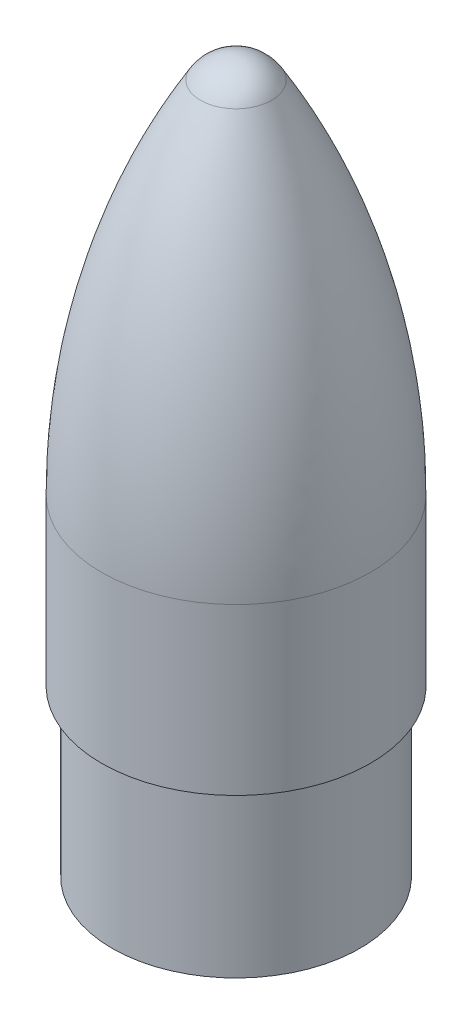
SolidWorks part; units mm, degrees
ref_plane "Front Plane" through (0, 0, 0) normal (0, 0, 1) x (1, 0, 0)
ref_plane "Top Plane" through (0, 0, 0) normal (0, 1, 0) x (1, 0, 0)
ref_plane "Right Plane" through (0, 0, 0) normal (1, 0, 0) x (0, 0, -1)
sketch "Sketch1" plane through (0, 0, 0) normal (0, 1, 0) x (1, 0, 0)
  circle A0 centre (0, 0) radius 38.1
  dimension "D1" = 76.2
extrude "Boss-Extrude1" add sketch "Sketch1" along normal blind 50.8
sketch "Sketch2" plane through (0, 50.8, 0) normal (0, 1, 0) x (1, 0, 0)
  circle A0 centre (0, 0) radius 41.275
  dimension "D1" = 82.55
extrude "Boss-Extrude2" add sketch "Sketch2" along normal blind 50.8 contours A0
sketch "Sketch3" plane through (0, 0, 0) normal (0, 0, 1) x (1, 0, 0)
  line L0 (-41.275, 101.6) -> (-41.275, 203.5852) construction
  line L1 (0, 0) -> (0, 267.966) construction
  line L2 (41.275, 101.6) -> (-41.275, 101.6) construction
  line L3 (0, 214.4291) -> (0, 218.2391)
  line L4 (-41.275, 101.6) -> (-37.465, 101.6)
  line L6 (-37.465, 101.6) -> (-37.465, 203.5852) construction
  arc A2 (-8.1383, 210.2757) -> (0, 214.4291) centre (0, 204.3791) cw
  arc A3 (-10.9151, 212.0314) -> (0, 218.2391) centre (0, 205.539) cw
  spline S0 degree 4 poles (-40.9693, 90.1105) (-40.9822, 90.3534) (-41.0072, 90.8387) (-41.0544, 91.8015) (-41.1162, 93.2573) (-41.1671, 94.6789) (-41.2072, 96.1406) (-41.2386, 97.5282) (-41.2579, 98.8003) (-41.2701, 99.8349) (-41.276, 101.4722) (-41.275, 102.0721) (-41.2687, 103.5121) (-41.2579, 104.3192) (-41.2464, 105.1639) (-41.2283, 106.1358) (-41.2007, 107.3342) (-41.1598, 108.7297) (-41.1008, 110.3354) (-41.0296, 111.9467) (-40.9463, 113.5588) (-40.8509, 115.1695) (-40.7435, 116.7799) (-40.6241, 118.3892) (-40.4598, 120.3997) (-40.2386, 122.8103) (-39.9456, 125.6193) (-39.5628, 128.8241) (-38.8092, 134.4221) (-36.9677, 145.5703) (-33.4913, 160.5237) (-28.3081, 176.2638) (-22.4871, 190.021) (-18.4288, 198.3676) (-16.1932, 202.6623) (-14.6574, 205.4912) (-13.7817, 207.0667) (-13.1957, 208.106) (-12.7072, 208.9626) (-12.3111, 209.651) (-11.9204, 210.3248) (-11.5265, 210.9984) (-11.0305, 211.8381) (-10.7524, 212.3053) (-10.167, 213.2822) (-9.756, 213.9581) (-9.2497, 214.7865) (-8.7818, 215.5428) (-8.2917, 216.329) (-7.8068, 217.0987) (-7.1874, 218.0733) (-6.4361, 219.2403) (-5.8, 220.2132) (-5.2857, 220.99) (-5.0271, 221.3781) knots 0 0 0 0 0 0.007003 0.014005 0.02801 0.041762 0.048638 0.055514 0.069266 0.076142 0.083018 0.094423 0.100125 0.105828 0.11153 0.117233 0.128638 0.140293 0.151949 0.163604 0.17526 0.186915 0.198571 0.210226 0.221881 0.245192 0.268503 0.291814 0.315125 0.408368 0.594855 0.734721 0.792998 0.83962 0.862931 0.874586 0.885991 0.891694 0.897396 0.903099 0.908801 0.914504 0.920206 0.926814 0.933421 0.940028 0.946636 0.953243 0.959851 0.966458 0.973065 0.986533 1 1 1 1 1 construction
  spline S1 degree 4 poles (-41.275, 101.6) (-41.275, 101.9305) (-41.2736, 102.4056) (-41.2687, 103.5121) (-41.2579, 104.3192) (-41.2464, 105.1639) (-41.2283, 106.1358) (-41.2007, 107.3342) (-41.1598, 108.7297) (-41.1008, 110.3354) (-41.0296, 111.9467) (-40.9463, 113.5588) (-40.8509, 115.1695) (-40.7435, 116.7799) (-40.6241, 118.3892) (-40.4598, 120.3997) (-40.2386, 122.8103) (-39.9456, 125.6193) (-39.5628, 128.8241) (-38.8092, 134.4221) (-36.9677, 145.5703) (-33.4913, 160.5237) (-28.3081, 176.2638) (-22.4871, 190.021) (-18.4288, 198.3676) (-16.1932, 202.6623) (-14.6574, 205.4912) (-13.7817, 207.0667) (-13.1957, 208.106) (-12.7072, 208.9626) (-12.3111, 209.651) (-11.9204, 210.3248) (-11.5265, 210.9984) (-11.1687, 211.6042) (-10.9996, 211.8893) (-10.9151, 212.0314) knots 0.083018 0.083018 0.083018 0.083018 0.083018 0.094423 0.100125 0.105828 0.11153 0.117233 0.128638 0.140293 0.151949 0.163604 0.17526 0.186915 0.198571 0.210226 0.221881 0.245192 0.268503 0.291814 0.315125 0.408368 0.594855 0.734721 0.792998 0.83962 0.862931 0.874586 0.885991 0.891694 0.897396 0.903099 0.908801 0.914504 0.920206 0.920206 0.920206 0.920206 0.920206
  spline S3 degree 4 poles (-37.465, 101.6) (-37.465, 101.9305) (-37.4636, 102.4056) (-37.4587, 103.5121) (-37.4479, 104.3192) (-37.4364, 105.1639) (-37.4183, 106.1358) (-37.3907, 107.3342) (-37.3498, 108.7297) (-37.2908, 110.3354) (-37.2196, 111.9467) (-37.1363, 113.5588) (-37.0409, 115.1695) (-36.9335, 116.7799) (-36.8141, 118.3892) (-36.6498, 120.3997) (-36.4286, 122.8103) (-36.1356, 125.6193) (-35.7528, 128.8241) (-34.9992, 134.4221) (-33.1577, 145.5703) (-29.6813, 160.5237) (-24.4981, 176.2638) (-18.6771, 190.021) (-14.6188, 198.3676) (-12.3832, 202.6623) (-10.8474, 205.4912) (-9.9717, 207.0667) (-9.3857, 208.106) (-8.8972, 208.9626) (-8.5578, 209.5524) (-8.3202, 209.9629) (-8.1803, 210.2035) (-8.1383, 210.2757) knots 0.083018 0.083018 0.083018 0.083018 0.083018 0.094423 0.100125 0.105828 0.11153 0.117233 0.128638 0.140293 0.151949 0.163604 0.17526 0.186915 0.198571 0.210226 0.221881 0.245192 0.268503 0.291814 0.315125 0.408368 0.594855 0.734721 0.792998 0.83962 0.862931 0.874586 0.885991 0.891694 0.897396 0.903099 0.905534 0.905534 0.905534 0.905534 0.905534
  point P3 (0, 0)
  point P5 (0, 218.2391)
  point P12 (-10.9151, 212.0314)
  dimension "D1" = 3.81
  dimension "D2" = 116.6391
  dimension "D3" = 3.81
revolve "Revolve17" add sketch "Sketch3" angle 360 about L1
